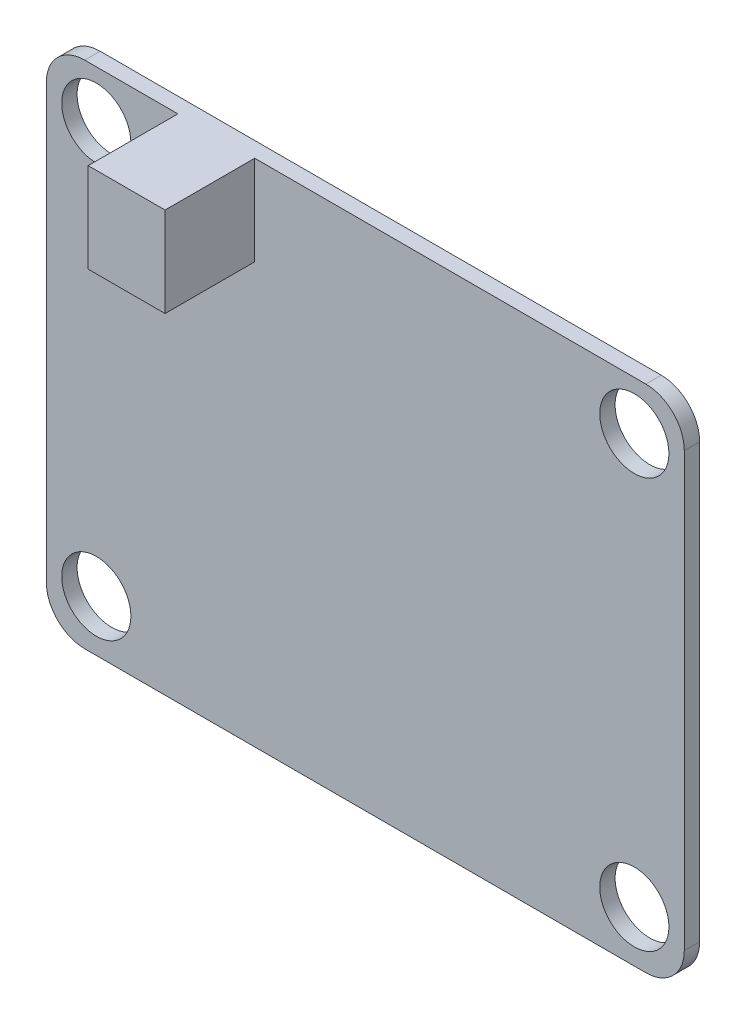
SolidWorks part; units mm, degrees
ref_plane "Alzado" through (0, 0, 0) normal (0, 0, 1) x (1, 0, 0)
ref_plane "Planta" through (0, 0, 0) normal (0, 1, 0) x (1, 0, 0)
ref_plane "Vista lateral" through (0, 0, 0) normal (1, 0, 0) x (0, 0, -1)
sketch "Croquis1" plane through (0, 0, 0) normal (0, 0, 1) x (1, 0, 0)
  line L1 (-56.8634, 16.1421) -> (-7.0634, 16.1421)
  line L2 (-56.8634, 16.1421) -> (-56.8634, -23.6579)
  line L3 (-56.8634, -23.6579) -> (-7.0634, -23.6579)
  line L4 (-7.0634, 16.1421) -> (-7.0634, -23.6579)
  circle A0 centre (-52.9634, 12.3421) radius 2.7
  circle A1 centre (-10.9634, 12.3421) radius 2.7
  circle A2 centre (-10.9634, -19.6579) radius 2.7
  circle A3 centre (-52.9634, -19.6579) radius 2.7
  dimension "D3" = 3.8
  dimension "D7" = 5.4
  dimension "D1" = 49.8
  dimension "D2" = 39.8
  dimension "D4" = 3.9
  dimension "D5" = 2
  dimension "D6" = 2
extrude "Saliente-Extruir1" add sketch "Croquis1" along normal blind 1.2
fillet "Redondeo1" radius 3 4 edges at (-7.0634, 16.1421, 0.6) (-56.8634, 16.1421, 0.6) (-7.0634, -23.6579, 0.6) (-56.8634, -23.6579, 0.6)
sketch "Croquis2" plane through (0, 0, 1.2) normal (0, 0, 1) x (1, 0, 0)
  line L0 (-10.0634, 16.1421) -> (-53.8634, 16.1421) construction
  line L1 (-40.5956, 16.1421) -> (-46.5956, 16.1421)
  line L2 (-40.5956, 16.1421) -> (-40.5956, 9.1421)
  line L3 (-40.5956, 9.1421) -> (-46.5956, 9.1421)
  line L4 (-46.5956, 16.1421) -> (-46.5956, 9.1421)
  dimension "D1" = 6
  dimension "D2" = 7
extrude "Saliente-Extruir2" add sketch "Croquis2" along normal blind 7
